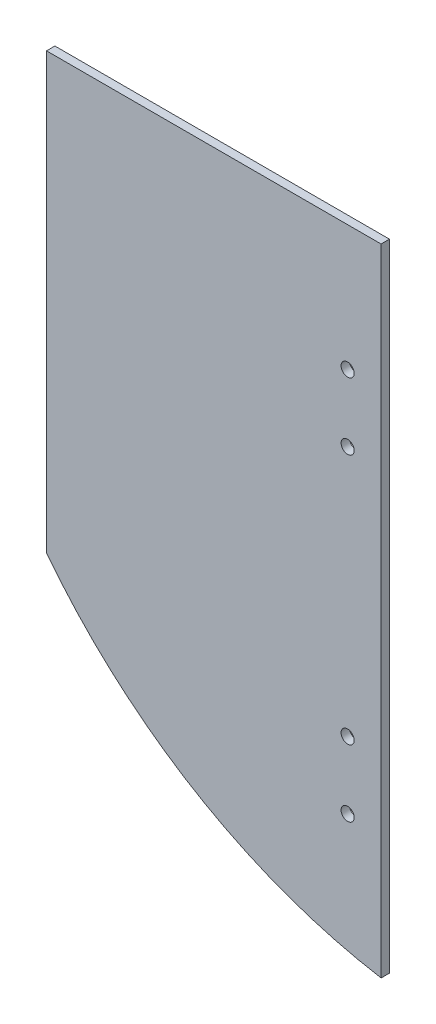
SolidWorks part; units mm, degrees
ref_plane "Front Plane" through (0, 0, 0) normal (1, 0, 0) x (0, 1, 0)
ref_plane "Top Plane" through (0, 0, 0) normal (0, 0, 1) x (0, 1, 0)
ref_plane "Right Plane" through (0, 0, 0) normal (0, 1, 0) x (-1, 0, 0)
sketch "Sketch1" plane through (0, 0, 0) normal (0, 0, 1) x (0, 1, 0)
  line L1 (-120.65, -63.5) -> (120.65, -63.5)
  line L2 (-120.65, -63.5) -> (-120.65, 63.5)
  line L3 (-120.65, 63.5) -> (120.65, 63.5)
  line L4 (120.65, -63.5) -> (120.65, 63.5)
  line L5 (-120.65, -63.5) -> (120.65, 63.5) construction
  line L6 (-120.65, 63.5) -> (120.65, -63.5) construction
  point P1 (0, 0)
  dimension "D1" = 241.3
  dimension "D2" = 127
extrude "Boss-Extrude1" add sketch "Sketch1" along normal blind 3.175
sketch "Sketch2" plane through (0, 0, 3.175) normal (0, 0, 1) x (1, 0, 0)
  line L0 (50.8, -120.65) -> (50.8, 120.65) construction
  line L1 (-63.5, -120.65) -> (63.5, -120.65) construction
  line L2 (63.5, 120.65) -> (-63.5, 120.65) construction
  line L4 (50.8, -120.65) -> (50.8, -73.025) construction
  line L5 (50.8, -47.625) -> (50.8, 0) construction
  line L6 (50.8, 0) -> (50.8, 47.625) construction
  line L7 (50.8, 73.025) -> (50.8, 120.65) construction
  line L10 (63.5, -120.65) -> (63.5, 120.65) construction
  point P8 (50.8, -73.025)
  point P9 (50.8, -47.625)
  point P10 (50.8, 47.625)
  point P11 (50.8, 73.025)
  dimension "D1" = 12.7
  dimension "D2" = 25.4
  dimension "D3" = 25.4
hole_wizard "#9 (0.196) Diameter Hole1" positions "Sketch2" profile "Sketch3" hole size "#9" standard "ANSI Inch" end condition through all
sketch "Sketch3" plane through (50.8, 73.025, 3.175) normal (1, 0, 0) x (0, -1, 0)
  line L0 (0, 0) -> (0, 3.175)
  line L1 (0, 3.175) -> (2.4892, 3.175)
  line L2 (2.4892, 3.175) -> (2.4892, 0)
  line L5 (2.4892, 0) -> (0, 0)
  line L11 (0, -6.35) -> (0, 107.95) construction
  dimension "Thru Hole Dia." = 4.9784
  dimension "Thru Hole Depth" = 3.175
sketch "Sketch4" plane through (0, 0, 3.175) normal (0, 0, 1) x (1, 0, 0)
  line L6 (-63.5, -44.45) -> (-63.5, -120.65)
  line L7 (-63.5, -120.65) -> (63.5, -120.65)
  line L8 (-63.5, -120.65) -> (63.5, -120.65) construction
  arc A2 (-63.5, -44.45) -> (63.5, -120.65) centre (97.3558, 79.7097) ccw
  point P0 (46.1656, -120.65)
  dimension "D1" = 76.2
  dimension "D2" = 203.2
extrude "Cut-Extrude1" cut sketch "Sketch4" against normal through all
